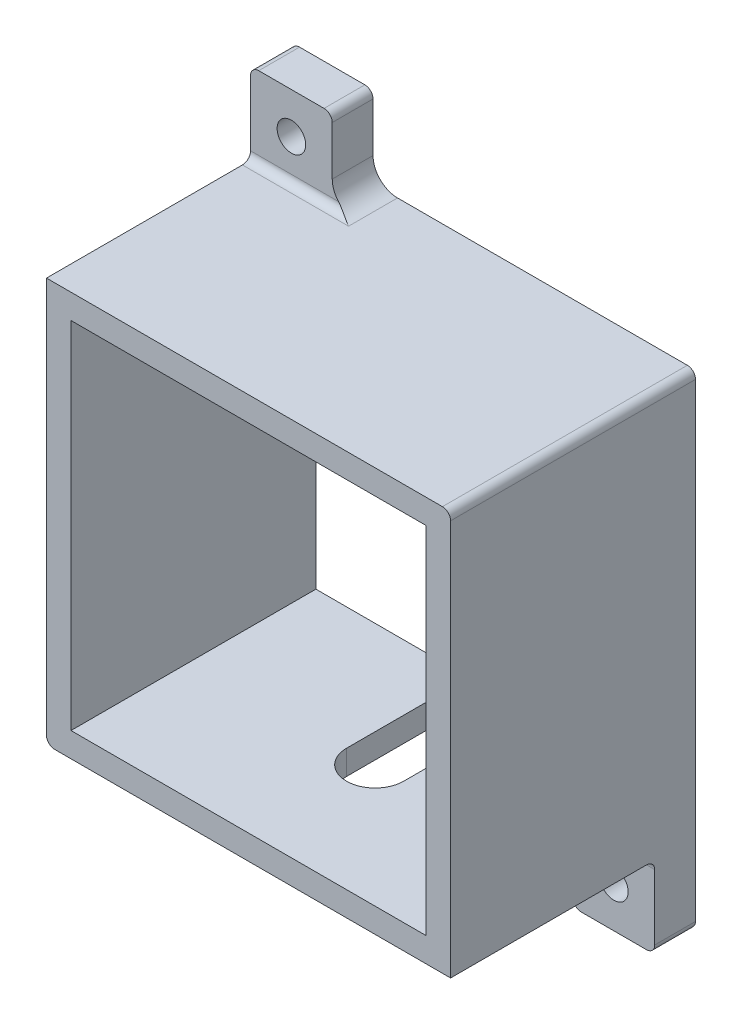
SolidWorks part; units mm, degrees
ref_plane "Plan de face" through (0, 0, 0) normal (0, 0, 1) x (1, 0, 0)
ref_plane "Plan de dessus" through (0, 0, 0) normal (0, 1, 0) x (1, 0, 0)
ref_plane "Plan de droite" through (0, 0, 0) normal (1, 0, 0) x (0, 0, -1)
sketch "Esquisse1" plane through (0, 0, 0) normal (0, 0, 1) x (1, 0, 0)
  line L1 (0, 0) -> (49.5, 0)
  line L2 (0, 0) -> (0, 49.5)
  line L3 (0, 49.5) -> (49.5, 49.5)
  line L4 (49.5, 0) -> (49.5, 49.5)
  line L5 (3, 3) -> (46.5, 3)
  line L6 (3, 3) -> (3, 46.5)
  line L7 (3, 46.5) -> (46.5, 46.5)
  line L8 (46.5, 3) -> (46.5, 46.5)
  dimension "D1" = 43.5
  dimension "D2" = 3
  dimension "D3" = 3
  dimension "D4" = 3
extrude "Boss.-Extru.1" add sketch "Esquisse1" along normal blind 30
sketch "Esquisse2" plane through (0, 0, 0) normal (0, 0, -1) x (-1, 0, 0)
  line L0 (-49.5, 0) -> (-39.5, -10) construction
  line L1 (0, 49.5) -> (-10, 49.5)
  line L2 (0, 49.5) -> (0, 59.5)
  line L3 (0, 59.5) -> (-10, 59.5)
  line L4 (-10, 49.5) -> (-10, 59.5)
  line L5 (-49.5, 0) -> (-39.5, 0)
  line L6 (-49.5, 0) -> (-49.5, -10)
  line L7 (-49.5, -10) -> (-39.5, -10)
  line L8 (-39.5, 0) -> (-39.5, -10)
  line L9 (-39.5, 0) -> (-49.5, -10) construction
  line L10 (-10, 59.5) -> (0, 49.5) construction
  line L11 (-10, 49.5) -> (0, 59.5) construction
  circle A0 centre (-5, 54.5) radius 1.75
  circle A1 centre (-44.5, -5) radius 1.75
  dimension "D2" = 3.5
  dimension "D1" = 10
extrude "Boss.-Extru.2" add sketch "Esquisse2" against normal blind 5
fillet "Congé1" radius 1 6 edges at (49.5, -10, 2.5) (39.5, -10, 2.5) (0, 0, 15) (49.5, 49.5, 15) (10, 59.5, 2.5) (0, 59.5, 2.5)
fillet "Congé2" radius 3 2 edges at (39.5, 0, 2.5) (10, 49.5, 2.5)
fillet "Congé3" radius 1 2 edges at (43, 0, 5) (6.5, 49.5, 5)
sketch "Sketch1" plane through (0, 0, 0) normal (0, -1, 0) x (1, 0, 0)
  line L0 (1, 15) -> (49.5, 15)
  line L1 (1, 30) -> (1, 0) construction
  line L2 (49.5, 30) -> (49.5, 6) construction
  line L3 (1, 15) -> (49.5, 15)
  line L4 (25.25, -15) -> (25.25, 15) construction
  line L5 (1, 0) -> (36.5, 0) construction
  line L6 (21.75, -15) -> (21.75, 15)
  line L7 (28.75, -15) -> (28.75, 15)
  arc A0 (21.75, -15) -> (28.75, -15) centre (25.25, -15) ccw
  arc A1 (28.75, 15) -> (21.75, 15) centre (25.25, 15) ccw
  point P10 (25.25, 0)
  line M9 (1, 0) -> (36.5, 0)
  dimension "D1" = 7
extrude "Cut-Extrude1" cut sketch "Sketch1" against normal blind 21.1716 and the other way blind 24 contours L3 L0 A1 | L4 L7 L0 M9 | L4 L3 L6 M9
